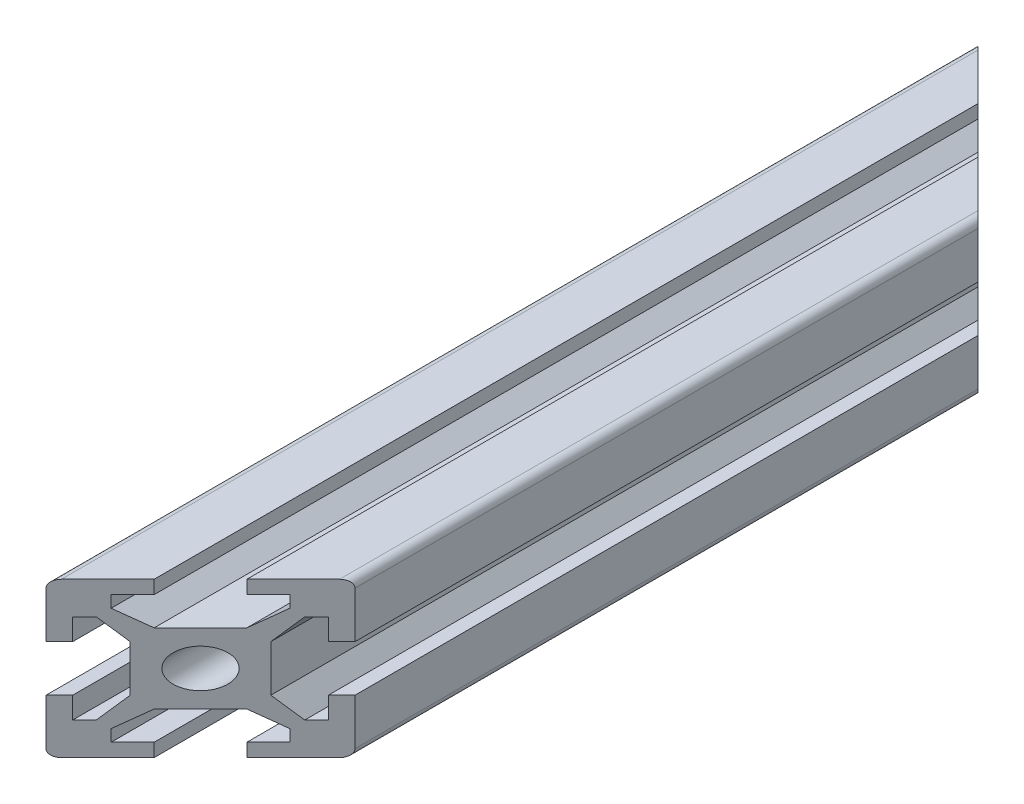
SolidWorks part; units mm, degrees
ref_plane "Front Plane" through (0, 0, 0) normal (0, 0, 1) x (1, 0, 0)
ref_plane "Top Plane" through (0, 0, 0) normal (0, 1, 0) x (1, 0, 0)
ref_plane "Right Plane" through (0, 0, 0) normal (1, 0, 0) x (0, 0, -1)
sketch "Sketch1" plane through (0, 0, 0) normal (0, 0, 1) x (1, 0, 0)
  line L18 (0, 0) -> (0, 20.5117) construction
  line L39 (-10, 10) -> (-3, 10)
  line L41 (10, 10) -> (3, 10)
  line L43 (-10, 10) -> (-10, 3)
  line L45 (-10, -10) -> (-10, -3)
  line L47 (-10, -10) -> (-3, -10)
  line L49 (3, -10) -> (10, -10)
  line L51 (10, -10) -> (10, -3)
  line L53 (10, 3) -> (10, 10)
  line L55 (-3, 10) -> (-3, 8.2726)
  line L56 (-3, 8.2726) -> (-5.7838, 8.2726)
  line L57 (-5.7838, 8.2726) -> (-5.7838, 6.748)
  line L58 (-5.7838, 6.748) -> (-3, 4.5508)
  line L59 (-3, 4.5508) -> (3, 4.5508)
  line L60 (3, 10) -> (3, 8.2726)
  line L61 (3, 8.2726) -> (5.7838, 8.2726)
  line L62 (5.7838, 8.2726) -> (5.7838, 6.748)
  line L63 (5.7838, 6.748) -> (3, 4.5508)
  line L64 (10, 3) -> (8.2726, 3)
  line L65 (8.2726, 3) -> (8.2726, 5.7838)
  line L66 (8.2726, 5.7838) -> (6.748, 5.7838)
  line L67 (10, -3) -> (8.2726, -3)
  line L68 (8.2726, -3) -> (8.2726, -5.7838)
  line L69 (8.2726, -5.7838) -> (6.748, -5.7838)
  line L70 (4.55, -2.9994) -> (4.55, 3.0006)
  line L71 (4.55, -2.9994) -> (6.748, -5.7838)
  line L72 (4.55, 3.0006) -> (6.748, 5.7838)
  line L73 (3, -10) -> (3, -8.2726)
  line L74 (3, -8.2726) -> (5.7838, -8.2726)
  line L75 (5.7838, -8.2726) -> (5.7838, -6.748)
  line L76 (-3, -10) -> (-3, -8.2726)
  line L77 (-3, -8.2726) -> (-5.7838, -8.2726)
  line L78 (-5.7838, -8.2726) -> (-5.7838, -6.748)
  line L79 (2.9994, -4.55) -> (-3.0006, -4.55)
  line L80 (5.7838, -6.748) -> (2.9994, -4.55)
  line L81 (-5.7838, -6.748) -> (-3.0006, -4.55)
  line L82 (-10, -3) -> (-8.2726, -3)
  line L83 (-8.2726, -3) -> (-8.2726, -5.7838)
  line L84 (-8.2726, -5.7838) -> (-6.748, -5.7838)
  line L85 (-10, 3) -> (-8.2726, 3)
  line L86 (-8.2726, 3) -> (-8.2726, 5.7838)
  line L87 (-8.2726, 5.7838) -> (-6.748, 5.7838)
  line L88 (-4.55, -3.0006) -> (-4.55, 2.9994)
  line L89 (-6.748, -5.7838) -> (-4.55, -3.0006)
  line L90 (-4.55, 2.9994) -> (-6.748, 5.7838)
  dimension "D9" = 7
  dimension "D17" = 2.7838
  dimension "D1" = 20
  dimension "D2" = 20
  dimension "D3" = 10
  dimension "D4" = 10
  dimension "D5" = 7
  dimension "D6" = 7
  dimension "D7" = 7
  dimension "D8" = 7
  dimension "D10" = 7
  dimension "D11" = 7
  dimension "D12" = 7
  dimension "D13" = 6
  dimension "D14" = 3
  dimension "D15" = 3.5464
  dimension "D16" = 1.5246
  dimension "D18" = 1.7274
  dimension "D19" = 4.55
  dimension "D20" = 4.55
  dimension "D21" = 4.55
  dimension "D22" = 10
  dimension "D23" = 10
  dimension "D24" = 10
  dimension "D25" = 10
  dimension "D26" = 10
  dimension "D27" = 10
  dimension "D28" = 6
  dimension "D29" = 6
  dimension "D30" = 6
  dimension "D31" = 6
extrude "Boss-Extrude1" add sketch "Sketch1" along normal mid plane 120.65
sketch "Sketch2" plane through (0, 0, 60.325) normal (0, 0, 1) x (1, 0, 0)
  circle A0 centre (0, 0) radius 2.5
  dimension "D1" = 5
extrude "Cut-Extrude1" cut sketch "Sketch2" against normal through all both and the other way through all
fillet "Fillet1" radius 1 4 edges at (-10, -10, 0) (10, -10, 0) (10, 10, 0) (-10, 10, 0)
ref_plane "Plane1" through (25.1625, 0, -25.1625) normal (-0.7071, 0, 0.7071) x (0.7071, 0, 0.7071)
sketch "Sketch3" plane through (25.1625, 0, -25.1625) normal (-0.7071, 0, 0.7071) x (0.7071, 0, 0.7071)
  line L0 (-49.7273, -3) -> (-49.7273, -9) construction
  line L1 (-54.8907, 11.0676) -> (-12.6118, 11.0676)
  line L2 (-54.8907, 11.0676) -> (-54.8907, -10.9324)
  line L3 (-54.8907, -10.9324) -> (-12.6118, -10.9324)
  line L4 (-12.6118, 11.0676) -> (-12.6118, -10.9324)
  line L5 (-49.0202, 10) -> (36.2923, 10) construction
  dimension "D1" = 22
  dimension "D2" = 42.2789
  dimension "D3" = 5.1634
  dimension "D4" = 1.0676
extrude "Cut-Extrude2" cut sketch "Sketch3" against normal through all
ref_plane "Plane2" through (25.1625, 0, 25.1625) normal (-0.7071, 0, -0.7071) x (-0.7071, 0, 0.7071)
sketch "Sketch4" plane through (25.1625, 0, 25.1625) normal (-0.7071, 0, -0.7071) x (-0.7071, 0, 0.7071)
  line L0 (49.7273, -3) -> (49.7273, -9) construction
  line L1 (54.6164, 11.0692) -> (19.6164, 11.0692)
  line L2 (54.6164, 11.0692) -> (54.6164, -11.0352)
  line L3 (54.6164, -11.0352) -> (19.6164, -11.0352)
  line L4 (19.6164, 11.0692) -> (19.6164, -11.0352)
  line L5 (49.0202, -10) -> (-35.5851, -10) construction
  dimension "D1" = 22.1045
  dimension "D2" = 35
  dimension "D3" = 4.8891
  dimension "D4" = 1.0352
extrude "Cut-Extrude3" cut sketch "Sketch4" against normal through all
